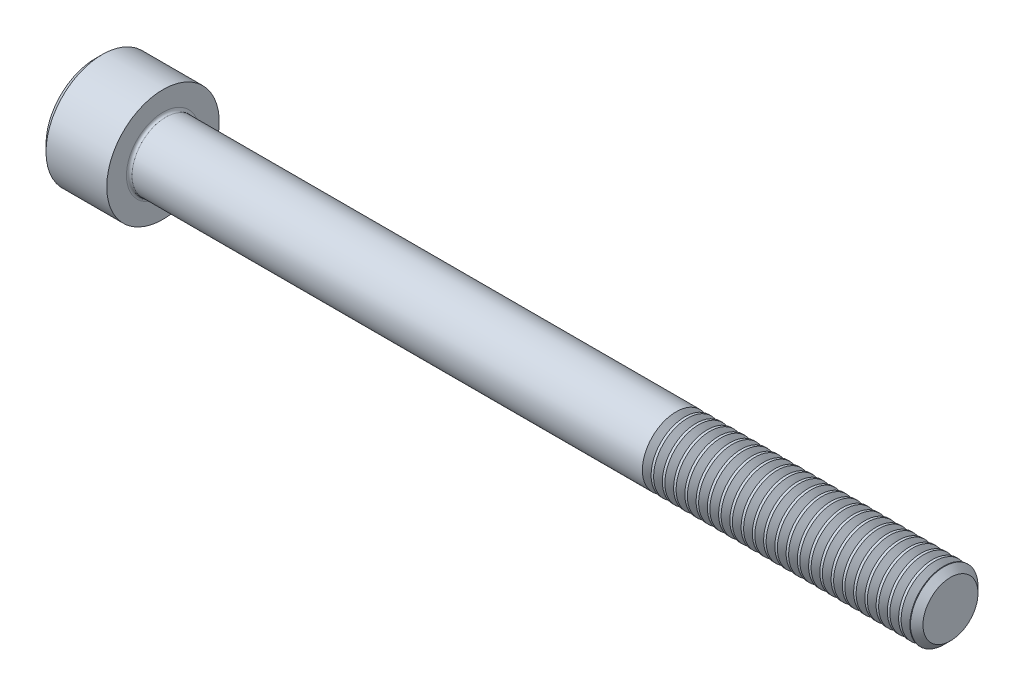
SolidWorks part; units mm, degrees
revolve "Base-Revolve" add sketch "BodySke"
sketch "BodySke" plane through (0, 0, 0) normal (0, 0, 1) x (1, 0, 0)
  line L0 (0, 0) -> (0, 4.4)
  line L1 (0.6, 5) -> (6, 5)
  line L2 (6, 5) -> (6, 3)
  line L3 (6, 3) -> (75.4455, 3)
  line L4 (76, 2.4455) -> (76, 0)
  line L5 (76, 0) -> (0, 0)
  line L6 (-31.75, 0) -> (127, 0) construction
  line L7 (0, 4.4) -> (0.6, 5)
  line L8 (76, 2.4455) -> (75.4455, 3)
  line L9 (0, -4.4) -> (0.6, -5) construction
  line L10 (76, -2.4455) -> (75.4455, -3) construction
  line L11 (7, 9.525) -> (7, 3.175) construction
  line L12 (52, 9.525) -> (52, 3.175) construction
  line L13 (26, 9.525) -> (26, 3.175) construction
  dimension "Diameter" = 6
  dimension "Head_ht" = 6
  dimension "Length" = 70
  dimension "Body_ch_ang" = 45
  dimension "Head_dia" = 10
  dimension "Head_ch_ang" = 45
  dimension "Minor_dia" = 4.891
  dimension "Advance" = 1
  dimension "Thread_nom" = 24
  dimension "Thread_length" = 50
  dimension "Head_ch_ht" = 0.6
cosmetic thread "ThreadCosmetic" [suppressed]
fillet "Fillet1" radius 0.25 1 edges at (6, 0, 3)
ref_plane "Plane1" through (0, 0, 0) normal (0, 0, 1) x (1, 0, 0)
ref_plane "Plane2" through (0, 0, 0) normal (0, 1, 0) x (1, 0, 0)
ref_plane "Plane3" through (0, 0, 0) normal (1, 0, 0) x (0, 0, -1)
sketch "Sketch2" plane through (0, 0, 0) normal (0, 0, 1) x (1, 0, 0)
  line L0 (0, 2.542) -> (3, 2.542)
  line L1 (3, 2.542) -> (4.4676, 0)
  line L2 (-31.75, 0) -> (127, 0) construction
  line L3 (4.4676, 0) -> (0, 0)
  line L4 (0, 0) -> (0, 2.542)
  line L5 (0, 4.4) -> (0, -4.4) construction
  line L6 (0, 0) -> (47.625, 0) construction
  line L7 (6, -5) -> (6, 5) construction
  dimension "D2" = 60
revolve "Hex-PreBroach" cut sketch "Sketch2" angle 360 about L6
sketch "Sketch3" plane through (0, 0, 0) normal (-1, 0, 0) x (0, 0.5, 0.866)
  line L0 (1.4676, 2.542) -> (-1.4676, 2.542)
  line L1 (-1.4676, 2.542) -> (-2.9352, 0)
  line L2 (1.4676, 2.542) -> (2.9352, 0)
  line L3 (1.4676, -2.542) -> (2.9352, 0)
  line L4 (1.4676, -2.542) -> (-1.4676, -2.542)
  line L5 (-1.4676, -2.542) -> (-2.9352, 0)
extrude "Hex" cut sketch "Sketch3" against normal blind 3
sketch "Sketch4" plane through (0, 0, 0) normal (-1, 0, 0) x (0, 0, 1)
  line L0 (0, 0) -> (2.8067, 0)
  line L1 (0, 0) -> (6.1484, 3.5498) construction
  line L2 (0, 0) -> (1.4033, 2.4307)
  line L3 (2.3336, 0.614) -> (2.6851, 0.817)
  line L4 (1.6986, 1.7139) -> (2.0501, 1.9169)
  arc A0 (2.3336, 0.614) -> (1.6986, 1.7139) centre (0, 0) ccw
  arc A1 (2.8067, 0) -> (2.6851, 0.817) centre (0, 0) ccw
  arc A2 (1.4033, 2.4307) -> (2.0501, 1.9169) centre (0, 0) cw
  dimension "D1" = 30
  dimension "D2" = 60
extrude "Spline" [suppressed] cut sketch "Sketch4" against normal blind 3
pattern_circular "CirPattern1" [suppressed] count 6 every 60
sketch "Sketch5" plane through (0, 0, 0) normal (0, 0, 1) x (1, 0, 0)
  line L0 (-31.75, 0) -> (127, 0) construction
  line L2 (0, 4.4) -> (0, -4.4) construction
  circle A0 centre (2.3, 0) radius 0.675
  dimension "Drilled_hole_dia" = 1.35
  dimension "Drilled_hole_loc" = 2.3
extrude "Hole" [suppressed] cut sketch "Sketch5" against normal through all and the other way through all
pattern_circular "Drilled-4" [suppressed] count 2 every 60
pattern_circular "Drilled-6" [suppressed] count 3 every 60
sketch "ThdSchSke" plane through (0, 0, 0) normal (0, 0, 1) x (1, 0, 0)
  line L0 (52, -2.4455) -> (51.6117, -3)
  line L1 (52, -2.4455) -> (52.3883, -3)
  line L2 (52.3883, -3) -> (52.3883, -3.75)
  line L3 (-3.175, 0) -> (5.1513, 0) construction
  line L5 (52.3883, -3.75) -> (51.6117, -3.75)
  line L6 (51.6117, -3.75) -> (51.6117, -3)
  line L7 (0, 4.4) -> (0, -4.4) construction
revolve "ThreadSchematic" cut sketch "ThdSchSke" angle 360 about L3
pattern_linear "ThdSchPat" count 24 spacing 1 along (1, 0, 0) of "ThreadSchematic"
equation "\"D2@Sketch3\" = \"Hex_size@Sketch3\" / 2"
equation "\"D1@Sketch3\" = \"Hex_size@Sketch3\" / 2"
equation "\"D1@Sketch2\" = \"Hex_size@Sketch3\" / 2"
equation "\"D3@Sketch4\" = \"Spline_p_dim@Sketch4\" / 2"
equation "\"Thread_minor@ThreadCosmetic\"  =  \"Minor_dia@BodySke\""
equation "\"D2@CirPattern1\" = 360 / \"Num_teeth@CirPattern1\""
equation "\"Wall_thickness@Sketch2\" = \"Head_ht@BodySke\" - \"Key_eng@Hex\""
equation "\"Thread_length@ThreadCosmetic\" = ((sgn( (\"Length@BodySke\" - \"Advance@BodySke\" ) - \"Thread_nom@BodySke\" )-1)*( (\"Length@BodySke\" - \"Advance@BodySke\" ) - \"Thread_nom@BodySke\" ))/-2+ \"Thread_nom@BodySke\""
equation "\"Thread_minor@ThdSchSke\" = \"Minor_dia@BodySke\""
equation "\"Diameter@ThdSchSke\" = \"Diameter@BodySke\""
equation "\"Overcut@ThdSchSke\" = \"Diameter@BodySke\" * 1.25"
equation "\"Start@ThdSchSke\" = \"Head_ht@BodySke\" + \"Length@BodySke\" - \"Thread_length@ThreadCosmetic\"  '---Non-countersunk---"
equation "\"Num_threads@ThdSchPat\" = int( \"Thread_length@ThreadCosmetic\" / \"Advance@BodySke\" + 0.999 )  + 1"
equation "\"Advance@ThdSchPat\" = \"Thread_length@ThreadCosmetic\" /  (\"Num_threads@ThdSchPat\" - 1) 'relax it"
equation "\"Num_threads@ThdSchPat\" = \"Num_threads@ThdSchPat\" - sgn( \"Num_threads@ThdSchPat\" - 1) '---chamfered tips only---"
